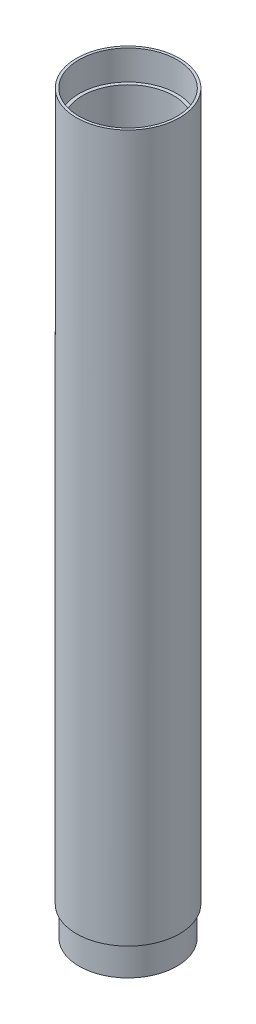
SolidWorks part; units mm, degrees
ref_plane "Front Plane" through (0, 0, 0) normal (0, 0, 1) x (1, 0, 0)
ref_plane "Top Plane" through (0, 0, 0) normal (0, 1, 0) x (1, 0, 0)
ref_plane "Right Plane" through (0, 0, 0) normal (1, 0, 0) x (0, 0, -1)
sketch "Sketch1" plane through (0, 0, 0) normal (0, 1, 0) x (1, 0, 0)
  circle A0 centre (0, 0) radius 15.5
  circle A1 centre (0, 0) radius 17.5
  dimension "D1" = 35
  dimension "D2" = 31
extrude "Boss-Extrude1" add sketch "Sketch1" along normal blind 240
sketch "Sketch2" plane through (0, 240, 0) normal (0, 1, 0) x (1, 0, 0)
  circle A1 centre (0, 0) radius 16.65
  circle A2 centre (0, 0) radius 17.5
  circle A3 centre (0, 0) radius 17.5
  dimension "D2" = 33.3
  dimension "D1" = 0
extrude "Boss-Extrude2" add sketch "Sketch2" along normal blind 10
sketch "Sketch3" plane through (0, 0, 0) normal (0, -1, 0) x (1, 0, 0)
  circle A2 centre (0, 0) radius 17.5
  circle A3 centre (0, 0) radius 17.5
  circle A4 centre (0, 0) radius 16.6
  dimension "D2" = 33.2
  dimension "D1" = 0
extrude "Cut-Extrude1" cut sketch "Sketch3" against normal blind 10
